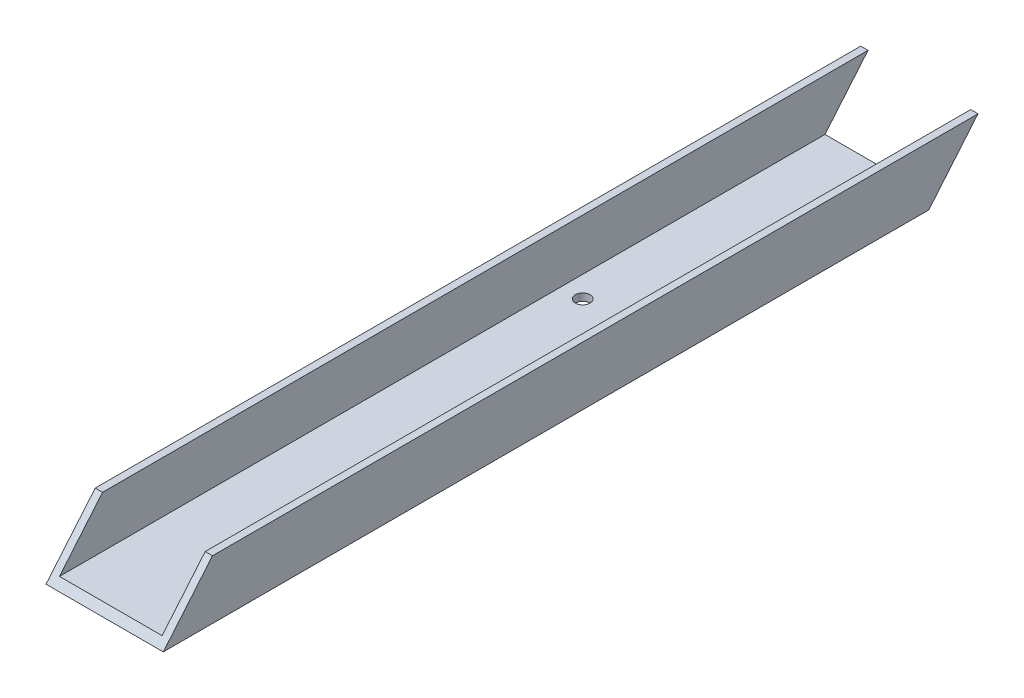
SolidWorks part; units mm, degrees
ref_plane "Front Plane" through (0, 0, 0) normal (0, 0, 1) x (1, 0, 0)
ref_plane "Top Plane" through (0, 0, 0) normal (0, 1, 0) x (1, 0, 0)
ref_plane "Right Plane" through (0, 0, 0) normal (1, 0, 0) x (0, 0, -1)
sketch "Sketch1" plane through (0, 0, 0) normal (0, 0, 1) x (1, 0, 0)
  line L0 (3.175, 3.175) -> (3.175, 25.4)
  line L1 (0, 0) -> (50.8, 0)
  line L2 (0, 0) -> (0, 25.4)
  line L3 (0, 25.4) -> (3.175, 25.4)
  line L4 (50.8, 0) -> (50.8, 25.4)
  line L5 (0, 0) -> (50.8, 25.4) construction
  line L6 (0, 25.4) -> (50.8, 0) construction
  line L7 (3.175, 3.175) -> (3.175, 22.225) construction
  line L8 (47.625, 3.175) -> (47.625, 25.4)
  line L9 (3.175, 3.175) -> (47.625, 3.175)
  line L10 (3.175, 22.225) -> (47.625, 22.225) construction
  line L11 (47.625, 3.175) -> (47.625, 22.225) construction
  line L12 (47.625, 25.4) -> (50.8, 25.4)
  line L13 (0, 25.4) -> (50.8, 25.4) construction
  point P4 (25.4, 12.7)
  dimension "D1" = 25.4
  dimension "D2" = 50.8
  dimension "D3" = 3.175
extrude "Boss-Extrude1" add sketch "Sketch1" along normal blind 457.2
sketch "Sketch2" plane through (0, 3.175, 0) normal (0, 1, 0) x (1, 0, 0)
  circle A1 centre (12.3849, -132.8188) radius 3.175
extrude "Cut-Extrude1" cut sketch "Sketch2" against normal up to next
sketch "Sketch3" plane through (0, 0, 0) normal (-1, 0, 0) x (0, 0, 1)
  line L0 (0, 25.4) -> (21.3131, 0)
  line L1 (457.2, 0) -> (0, 0) construction
  line L2 (21.3131, 0) -> (0, 0)
  line L3 (0, 0) -> (0, 25.4)
  dimension "D1" = 50
extrude "Cut-Extrude2" cut sketch "Sketch3" against normal through all
sketch "Sketch4" plane through (50.8, 0, 0) normal (1, 0, 0) x (0, 0, -1)
  line L1 (-352.8866, 0) -> (-331.5735, 25.4)
  line L2 (-457.2, 25.4) -> (-331.5735, 25.4)
  line L3 (-457.2, 25.4) -> (0, 25.4) construction
  line L4 (-457.2, 25.4) -> (-457.2, 0)
  line L5 (-457.2, 0) -> (-352.8866, 0)
  line L6 (-457.2, 0) -> (-21.3131, 0) construction
extrude "Cut-Extrude3" cut sketch "Sketch4" against normal through all
